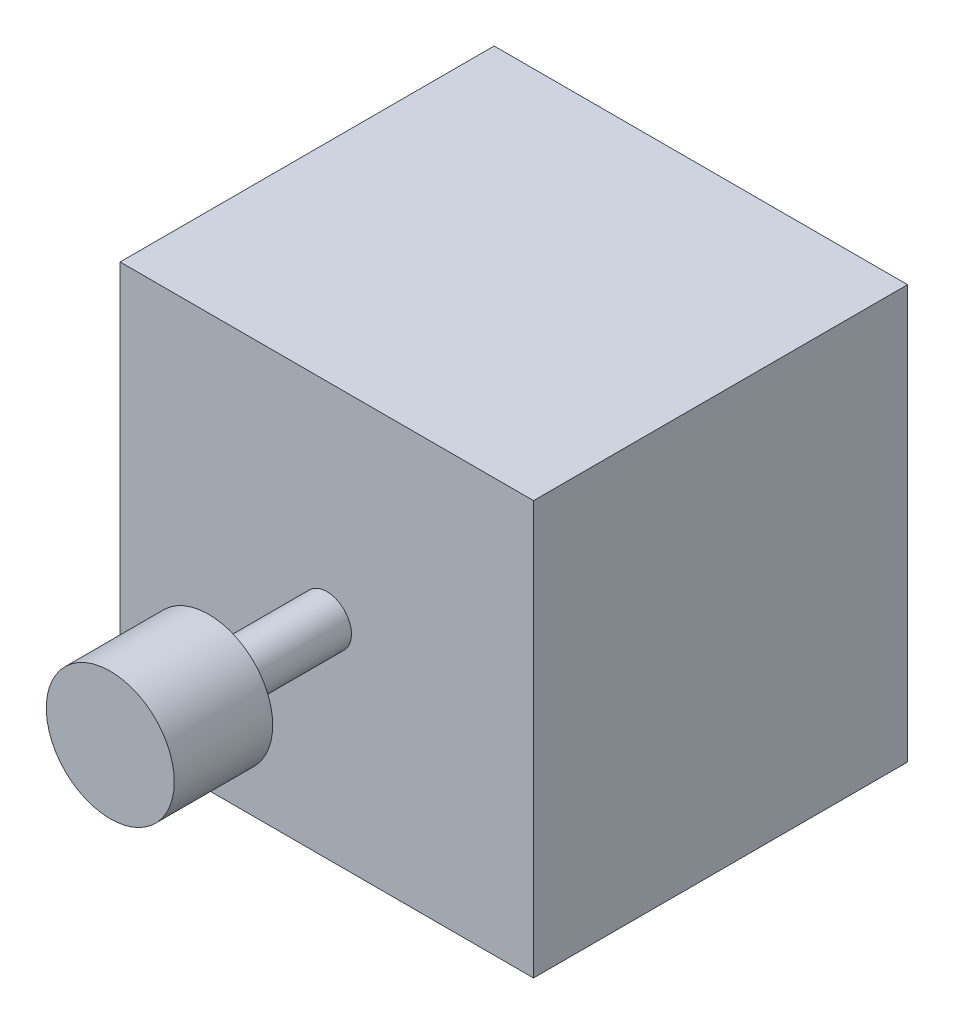
SolidWorks part; units mm, degrees
ref_plane "Front Plane" through (0, 0, 0) normal (0, 0, 1) x (1, 0, 0)
ref_plane "Top Plane" through (0, 0, 0) normal (0, 1, 0) x (1, 0, 0)
ref_plane "Right Plane" through (0, 0, 0) normal (1, 0, 0) x (0, 0, -1)
sketch "Sketch1" plane through (0, 0, 0) normal (0, 0, 1) x (1, 0, 0)
  line L1 (-21, 21) -> (21, 21)
  line L2 (-21, 21) -> (-21, -21)
  line L3 (-21, -21) -> (21, -21)
  line L4 (21, 21) -> (21, -21)
  line L5 (-21, 21) -> (21, -21) construction
  line L6 (-21, -21) -> (21, 21) construction
  point P0 (0, 0)
  dimension "D1" = 42
  dimension "D2" = 42
extrude "Boss-Extrude1" add sketch "Sketch1" along normal blind 38
sketch "Sketch2" plane through (0, 0, 38) normal (0, 0, 1) x (1, 0, 0)
  circle A0 centre (0, 0) radius 2.5
  dimension "D1" = 5
extrude "Boss-Extrude2" add sketch "Sketch2" along normal blind 22
sketch "Sketch3" plane through (0, 0, 60) normal (0, 0, 1) x (1, 0, 0)
  circle A0 centre (0, 0) radius 6.5
  dimension "D1" = 13
extrude "Boss-Extrude3" add sketch "Sketch3" against normal blind 10
